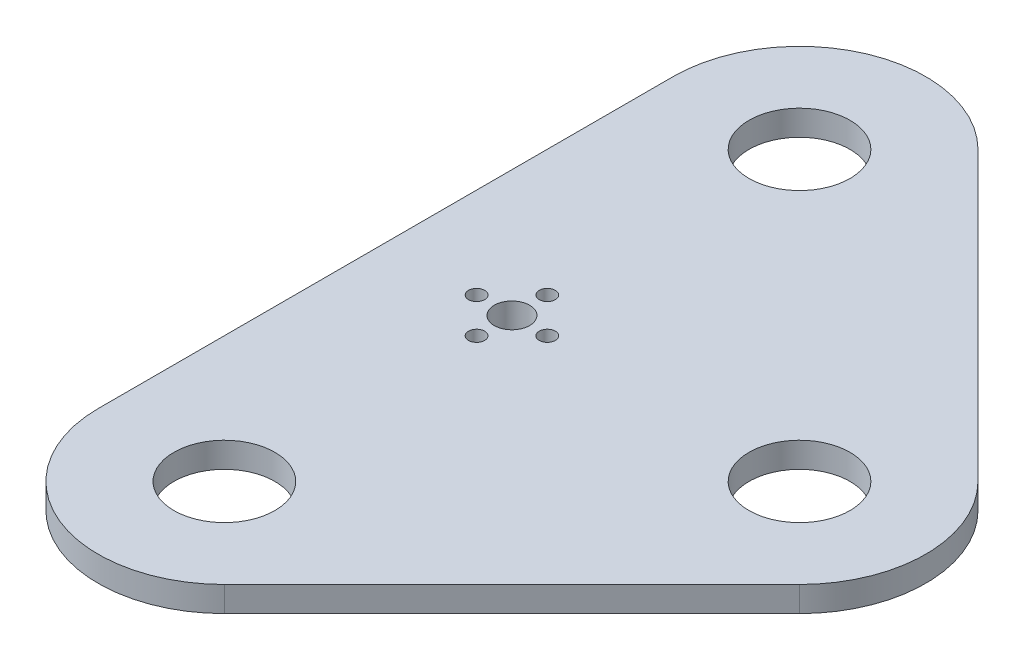
SolidWorks part; units mm, degrees
material "聚脂树脂"
ref_plane "前视基准面" through (0, 0, 0) normal (0, 0, 1) x (1, 0, 0)
ref_plane "上视基准面" through (0, 0, 0) normal (0, 1, 0) x (1, 0, 0)
ref_plane "右视基准面" through (0, 0, 0) normal (1, 0, 0) x (0, 0, -1)
other "Configuration Table"
sketch "草图1" plane through (0, 0, 0) normal (0, 1, 0) x (1, 0, 0)
  line L3 (0, 0) -> (0, 87.5857) construction
  line L4 (0, 0) -> (127.2008, 0) construction
  line L5 (-25, 56.96) -> (-25, -56.96)
  line L6 (17.6777, 74.6377) -> (74.6377, 17.6777)
  line L7 (17.6777, -74.6377) -> (74.6377, -17.6777)
  circle A3 centre (0, 0) radius 3.5
  circle A4 centre (0, 7) radius 1.6
  circle A5 centre (7, 0) radius 1.6
  circle A6 centre (-7, 0) radius 1.6
  circle A7 centre (0, -7) radius 1.6
  circle A8 centre (0, 56.96) radius 25
  circle A9 centre (56.96, 0) radius 25
  circle A10 centre (0, -56.96) radius 25
  circle A11 centre (0, 56.96) radius 10
  circle A12 centre (56.96, 0) radius 10
  circle A13 centre (0, -56.96) radius 10
  dimension "D2" = 3.2
  dimension "D3" = 7
  dimension "D4" = 7
  dimension "D1" = 3.2
  dimension "D5" = 7
  dimension "D6" = 113.92
  dimension "D7" = 56.96
  dimension "D8" = 50
  dimension "D9" = 50
  dimension "D10" = 20
  dimension "D11" = 20
  dimension "D12" = 20
extrude "凸台-拉伸1" add sketch "草图1" along normal blind 5 contours L5 A10 L7 A9 L6 A8 A6 A5 A4 A3 A7 | A10 A13 | A9 A12 | A8 A11
